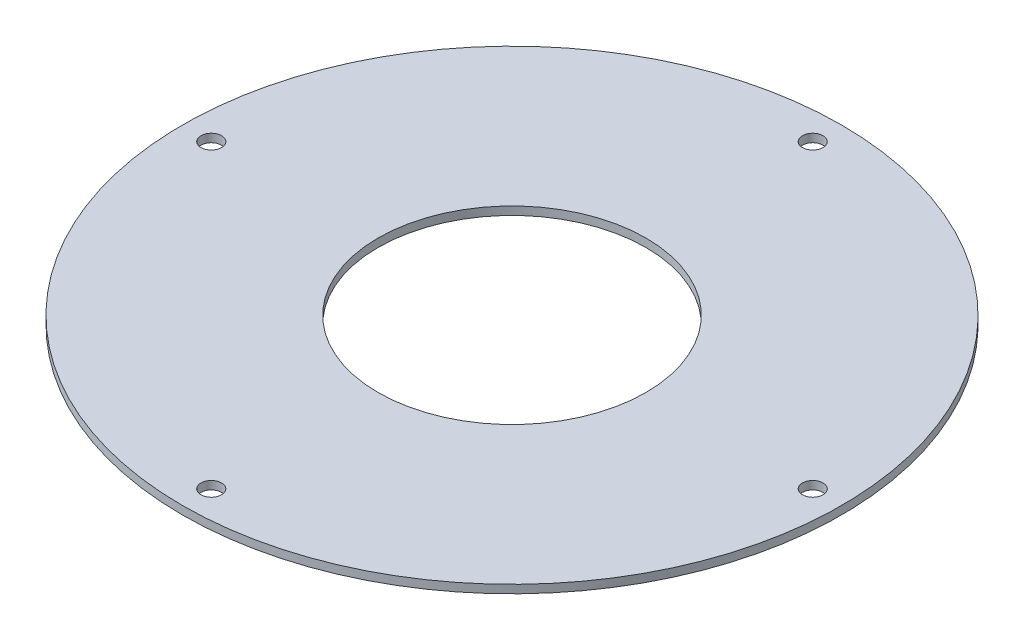
SolidWorks part; units mm, degrees
ref_plane "Front Plane" through (0, 0, 0) normal (0, 0, 1) x (1, 0, 0)
ref_plane "Top Plane" through (0, 0, 0) normal (0, 1, 0) x (1, 0, 0)
ref_plane "Right Plane" through (0, 0, 0) normal (1, 0, 0) x (0, 0, -1)
sketch "Sketch1" plane through (0, 0, 0) normal (0, 1, 0) x (1, 0, 0)
  circle A0 centre (0, 0) radius 80
  circle A1 centre (0, 0) radius 32.5
  dimension "D1" = 160
  dimension "D2" = 65
extrude "Boss-Extrude1" add sketch "Sketch1" along normal blind 2
sketch "Sketch2" plane through (0, 2, 0) normal (0, 1, 0) x (1, 0, 0)
  line L0 (0, 0) -> (0, 73) construction
  line L1 (0, 0) -> (73, 0) construction
  line L2 (0, 0) -> (0, -73) construction
  line L3 (0, 0) -> (-73, 0) construction
  circle A0 centre (0, 73) radius 2.5
  circle A1 centre (73, 0) radius 2.5
  circle A2 centre (0, -73) radius 2.5
  circle A3 centre (-73, 0) radius 2.5
  point P13 (0, 0)
  dimension "D2" = 5
  dimension "D1" = 73
  dimension "D3" = 4
extrude "Cut-Extrude1" cut sketch "Sketch2" against normal through all
